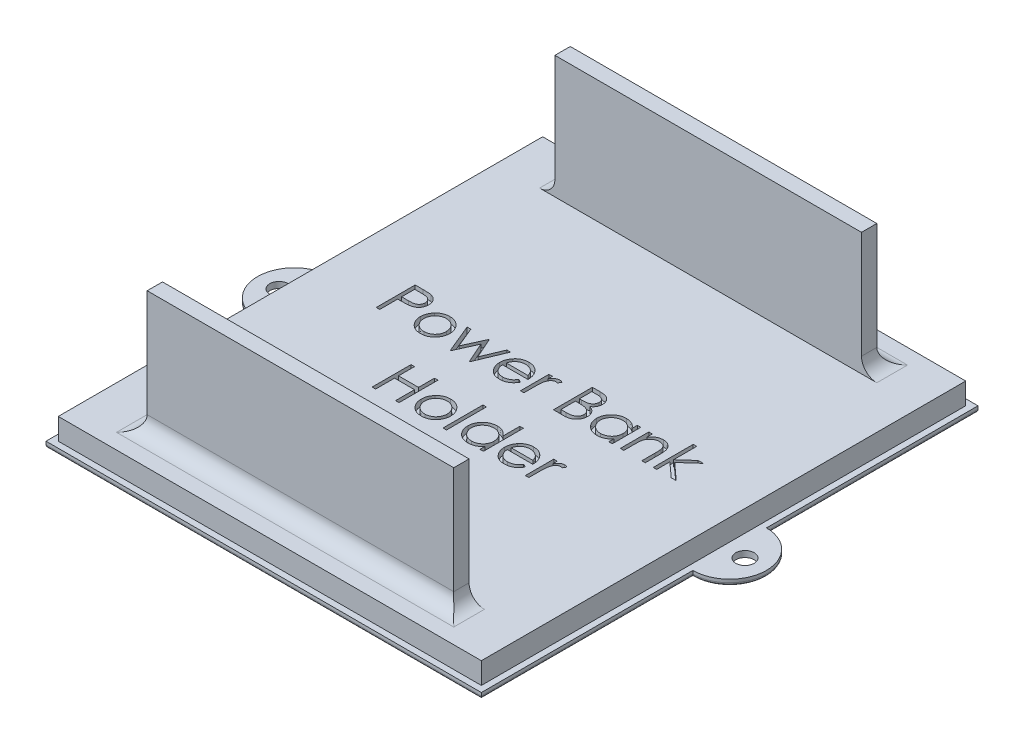
SolidWorks part; units mm, degrees
other "DetailItem2"
other "Markup1"
sketch "Sketch11" plane through (-41.5, 7, -35.5) normal (0, 1, 0) x (1, 0, 0)
sketch "Sketch12" plane through (-41.5, 7, -35.5) normal (0, 1, 0) x (1, 0, 0)
sketch "Sketch13" plane through (-41.5, 7, -35.5) normal (0, 1, 0) x (1, 0, 0)
sketch "Sketch15" plane through (-41.5, 7, -35.5) normal (0, 1, 0) x (1, 0, 0)
sketch "Sketch16" plane through (-41.5, 7, -35.5) normal (0, 1, 0) x (1, 0, 0)
sketch "Sketch17" plane through (-41.5, 7, -35.5) normal (0, 1, 0) x (1, 0, 0)
sketch "Sketch18" plane through (-41.5, 7, -35.5) normal (0, 1, 0) x (1, 0, 0)
sketch "Sketch19" plane through (-41.5, 7, -35.5) normal (0, 1, 0) x (1, 0, 0)
sketch "Sketch20" plane through (-41.5, 12, -35.5) normal (0, 1, 0) x (1, 0, 0)
sketch "Sketch21" plane through (-41.5, 25.5, -40.5) normal (0, 1, 0) x (1, 0, 0)
sketch "Sketch32" plane through (-41.5, 25.5, -40.5) normal (0, 1, 0) x (1, 0, 0)
sketch "Sketch36" plane through (-41.5, 25.5, -40.5) normal (0, 1, 0) x (1, 0, 0)
sketch "Sketch39" plane through (-41.5, 25.5, -40.5) normal (0, 1, 0) x (1, 0, 0)
sketch "Sketch42" plane through (-41.5, 25.5, -40.5) normal (0, 1, 0) x (1, 0, 0)
sketch "Sketch45" plane through (-41.5, 25.5, -35.5) normal (0, 1, 0) x (1, 0, 0)
sketch "Sketch55" plane through (-41.5, 25.5, -35.5) normal (0, 1, 0) x (1, 0, 0)
sketch "Sketch58" plane through (-41.5, 25.5, -35.5) normal (0, 1, 0) x (1, 0, 0)
other "Markup2"
sketch "Sketch37" plane through (41.5, 0.9701, -40.5) normal (1, 0, 0) x (0, 0, -1)
sketch "Sketch40" plane through (41.5, 0.9701, -40.5) normal (1, 0, 0) x (0, 0, -1)
sketch "Sketch43" plane through (41.5, 0.9701, -40.5) normal (1, 0, 0) x (0, 0, -1)
sketch "Sketch46" plane through (41.5, 0, -35.5) normal (1, 0, 0) x (0, 0, -1)
sketch "Sketch56" plane through (41.5, 0.9701, -35.5) normal (1, 0, 0) x (0, 0, -1)
sketch "Sketch59" plane through (41.5, 0.9701, -35.5) normal (1, 0, 0) x (0, 0, -1)
other "Markup3"
sketch "Sketch38" plane through (-41.5, 25.5, -40.5) normal (0, 1, 0) x (0, 0, -1)
sketch "Sketch41" plane through (-41.5, 25.5, -40.5) normal (0, 1, 0) x (0, 0, -1)
sketch "Sketch44" plane through (-41.5, 25.5, -40.5) normal (0, 1, 0) x (0, 0, -1)
sketch "Sketch47" plane through (-41.5, 25.5, -35.5) normal (0, 1, 0) x (0, 0, -1)
sketch "Sketch57" plane through (-41.5, 25.5, -35.5) normal (0, 1, 0) x (0, 0, -1)
sketch "Sketch60" plane through (-41.5, 25.5, -35.5) normal (0, 1, 0) x (0, 0, -1)
ref_plane "Front Plane" through (0, 0, 0) normal (0, 0, 1) x (1, 0, 0)
ref_plane "Top Plane" through (0, 0, 0) normal (0, 1, 0) x (1, 0, 0)
ref_plane "Right Plane" through (0, 0, 0) normal (1, 0, 0) x (0, 0, -1)
sketch "Sketch1" plane through (0, 0, 0) normal (0, 1, 0) x (1, 0, 0)
  line L1 (-35.5, -40.5) -> (35.5, -40.5)
  line L2 (-35.5, -40.5) -> (-35.5, 40.5)
  line L3 (-35.5, 40.5) -> (35.5, 40.5)
  line L4 (35.5, -40.5) -> (35.5, 40.5)
  line L5 (-35.5, -40.5) -> (35.5, 40.5) construction
  line L6 (-35.5, 40.5) -> (35.5, -40.5) construction
  point P0 (0, 0)
  dimension "D1" = 81
  dimension "D2" = 71
extrude "Boss-Extrude1" add sketch "Sketch1" along normal blind 4.5
sketch "Sketch4" plane through (0, 4.5, 0) normal (0, 1, 0) x (1, 0, 0)
  line L0 (-35.5, 40.5) -> (-35.5, -40.5) construction
  line L1 (-35.5, 6) -> (-35.5, -6)
  arc A0 (-35.5, 6) -> (-35.5, -6) centre (-35.5, 0) ccw
  dimension "D1" = 6
extrude "Boss-Extrude3" add sketch "Sketch4" against normal up to surface (4.5 mm away) up to face at (0, 0, 0)
sketch "Sketch5" plane through (0, 4.5, 0) normal (0, 1, 0) x (1, 0, 0)
  line L0 (-35.5, 40.5) -> (-35.5, 6) construction
  circle A0 centre (-38, 0) radius 1.5
  dimension "D1" = 3
  dimension "D2" = 2.5
extrude "Cut-Extrude2" cut sketch "Sketch5" against normal up to surface (4.5 mm away) up to face at (-12.8333, 0, 0)
mirror "Mirror3" about plane through (0, 0, 0) normal (1, 0, 0) of "Boss-Extrude3", "Cut-Extrude2"
sketch "Sketch61" plane through (0, 4.5, 0) normal (0, 1, 0) x (1, 0, 0)
  line L0 (35.5, 6) -> (35.5, 40.5) construction
  line L1 (-34.5, -39.5) -> (34.5, -39.5)
  line L2 (-34.5, -39.5) -> (-34.5, 39.5)
  line L3 (-34.5, 39.5) -> (34.5, 39.5)
  line L4 (34.5, -39.5) -> (34.5, 39.5)
  line L5 (-34.5, -39.5) -> (34.5, 39.5) construction
  line L6 (-34.5, 39.5) -> (34.5, -39.5) construction
  line L7 (35.5, 40.5) -> (-35.5, 40.5) construction
  line L8 (-44.5, 49.5) -> (44.5, 49.5)
  line L9 (44.5, -49.5) -> (44.5, 49.5)
  line L10 (-44.5, -49.5) -> (44.5, -49.5)
  line L11 (-44.5, -49.5) -> (-44.5, 49.5)
  point P0 (0, 0)
  dimension "D1" = 1
  dimension "D2" = 1
  dimension "D3" = 10
extrude "Cut-Extrude21" cut sketch "Sketch61" against normal offset from surface (3.5 mm away) 1 up to face at (38, 0, -1.5)
sketch "text" plane through (0, 4.5, 0) normal (0, 1, 0) x (1, 0, 0)
  line L0 (-35.4043, 1.8177) -> (35.5957, 1.8177) construction
  text T0 "Power Bank\r\nHolder" font "Century Gothic" height in points 24
extrude "Cut-Extrude1" cut sketch "text" against normal blind 1
sketch "Sketch9" plane through (0, 4.5, 0) normal (0, 1, 0) x (1, 0, 0)
  line L1 (-25, 34.5) -> (25, 34.5)
  line L2 (-25, 34.5) -> (-25, 32)
  line L3 (-25, 32) -> (25, 32)
  line L4 (25, 34.5) -> (25, 32)
  point P4 (0, 32)
  dimension "D1" = 50
  dimension "D2" = 2.5
  dimension "D3" = 32
extrude "top track" add sketch "Sketch9" along normal blind 20 contours L2 L1 L4 L3
fillet "Fillet1" radius 2.5 3 edges at (25, 4.5, -33.25) (0, 4.5, -34.5) (-25, 4.5, -33.25)
mirror "Mirror4" about plane through (0, 0, 0) normal (0, 0, 1) of "top track", "Fillet1"
fillet "Fillet2" radius 0.5 8 edges at (35.5, 0, 23.25) (41.5, 0, 0) (35.5, 0, -23.25) (0, 0, -40.5) (-35.5, 0, -23.25) (-41.5, 0, 0) (-35.5, 0, 23.25) (0, 0, 40.5)
equation "\"Screw_Diameter\"=3"
